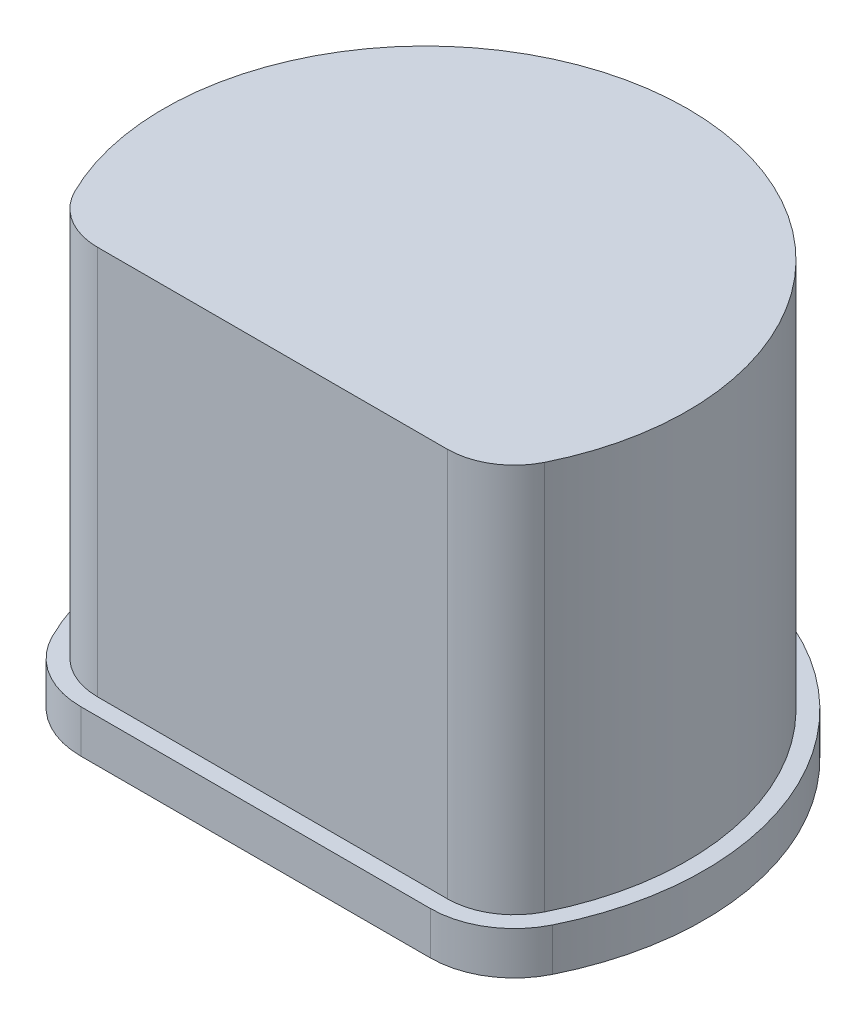
SolidWorks part; units mm, degrees
ref_plane "Front Plane" through (0, 0, 0) normal (0, 0, 1) x (1, 0, 0)
ref_plane "Top Plane" through (0, 0, 0) normal (0, 1, 0) x (1, 0, 0)
ref_plane "Right Plane" through (0, 0, 0) normal (1, 0, 0) x (0, 0, -1)
sketch "Sketch1" plane through (0, 0, 0) normal (0, 1, 0) x (1, 0, 0)
  line L0 (-6.5292, -5.72) -> (6.5292, -5.72)
  arc A0 (8.7713, -4.3258) -> (-8.7713, -4.3258) centre (0, 0) ccw
  arc A1 (-6.5292, -5.72) -> (-8.7713, -4.3258) centre (-6.5292, -3.22) cw
  arc A2 (8.7713, -4.3258) -> (6.5292, -5.72) centre (6.5292, -3.22) cw
  point P5 (0, 9.78)
  dimension "D1" = 15.5
extrude "Boss-Extrude1" add sketch "Sketch1" along normal blind 14.54
sketch "Sketch3" plane through (0, 0, 0) normal (0, -1, 0) x (1, 0, 0)
  line L1 (-6.5292, 5.72) -> (6.5292, 5.72) construction
  line L2 (6.5292, 6.35) -> (-6.5292, 6.35)
  arc A3 (-9.3363, 4.6044) -> (-6.5292, 6.35) centre (-6.5292, 3.22) cw
  arc A4 (-9.3363, 4.6044) -> (9.3363, 4.6044) centre (0, 0) ccw
  arc A5 (6.5292, 6.35) -> (9.3363, 4.6044) centre (6.5292, 3.22) cw
extrude "Boss-Extrude2" add sketch "Sketch3" along normal blind 1.6
sketch "Sketch8" plane through (0, 14.54, 0) normal (0, 1, 0) x (1, 0, 0)
  line L0 (-6.5292, -4.37) -> (6.5292, -4.37)
  arc A0 (7.5606, -3.7287) -> (6.5292, -4.37) centre (6.5292, -3.22) cw
  arc A1 (7.5606, -3.7287) -> (-7.5606, -3.7287) centre (0, 0) ccw
  arc A2 (-6.5292, -4.37) -> (-7.5606, -3.7287) centre (-6.5292, -3.22) cw
extrude "Cut-Extrude1" [suppressed] cut sketch "Sketch8" against normal offset from surface (15.14 mm away) 1
fillet "Fillet1" [suppressed] radius 0.3
sketch "Sketch5" plane through (0, -1.6, 0) normal (0, -1, 0) x (1, 0, 0)
  line L1 (6.175, -2.05) -> (-6.175, -2.05)
  line L2 (6.175, -2.05) -> (6.175, 2.05)
  line L3 (6.175, 2.05) -> (-6.175, 2.05)
  line L4 (-6.175, -2.05) -> (-6.175, 2.05)
  point P4 (0, 2.05)
  point P5 (-6.175, 0)
  dimension "D1" = 12.35
  dimension "D2" = 4.1
  dimension "D3" = 0
  dimension "D4" = 0
extrude "Boss-Extrude3" add sketch "Sketch5" along normal blind 2.45
sketch "Sketch6" plane through (0, -4.05, 0) normal (0, -1, 0) x (1, 0, 0)
  circle A0 centre (0, 0) radius 1
  circle A1 centre (4, 0) radius 1
  circle A2 centre (-4, 0) radius 1
  dimension "D1" = 4
  dimension "D2" = 4
extrude "Pins" [suppressed] add sketch "Sketch6" against normal blind 15
fillet "Fillet3" [suppressed] radius 1
sketch "Sketch7" plane through (0, 0, 0) normal (0, 1, 0) x (1, 0, 0)
  line L1 (-5.909, -2.27) -> (5.909, -2.27)
  circle A0 centre (0, 0) radius 1.2
  circle A1 centre (4, 0) radius 1.2
  circle A2 centre (-4, 0) radius 1.2
  arc A4 (5.909, -2.27) -> (-5.909, -2.27) centre (0, 0) ccw
  dimension "D1" = 4
  dimension "D2" = 4
extrude "Boss-Extrude5" [suppressed] add sketch "Sketch7" along normal blind 13
